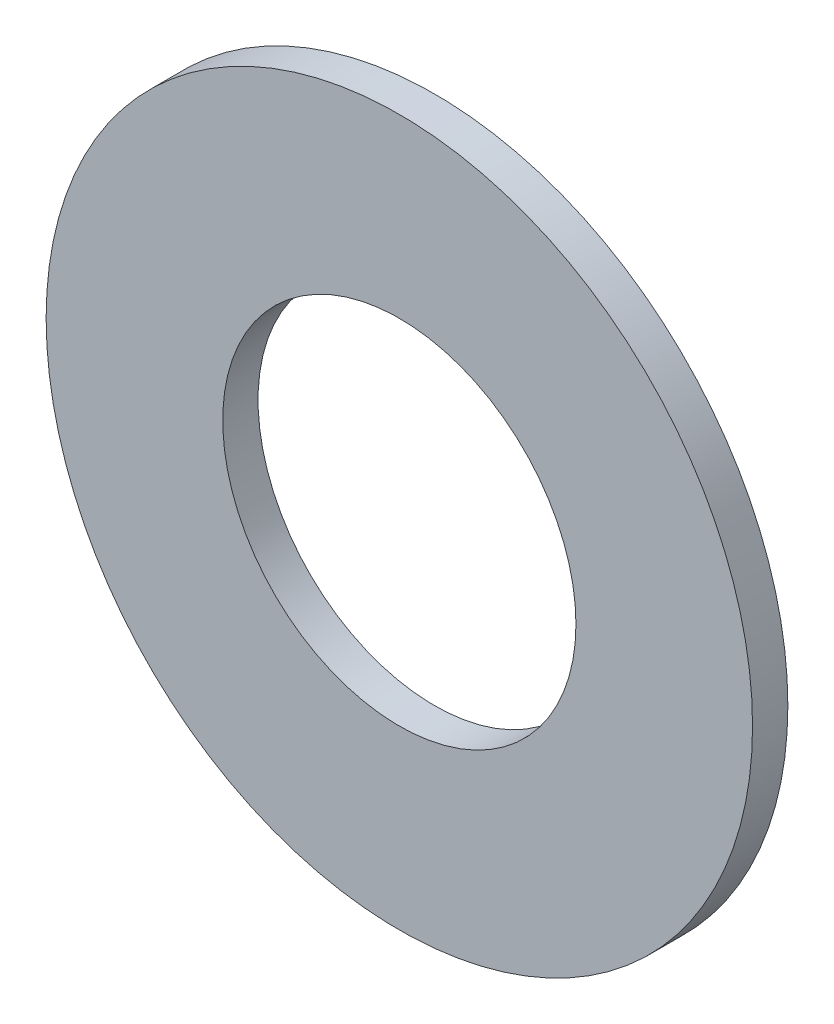
SolidWorks part; units mm, degrees
material "Литая нержавеющая сталь"
ref_plane "Спереди" through (0, 0, 0) normal (0, 0, 1) x (1, 0, 0)
ref_plane "Сверху" through (0, 0, 0) normal (0, 1, 0) x (1, 0, 0)
ref_plane "Справа" through (0, 0, 0) normal (1, 0, 0) x (0, 0, -1)
sketch "Эскиз1" plane through (0, 0, 0) normal (0, 0, 1) x (1, 0, 0)
  circle A0 centre (0, 0) radius 20
  circle A1 centre (0, 0) radius 10
  dimension "D1" = 20
  dimension "D2" = 40
extrude "Вытянуть1" add sketch "Эскиз1" along normal blind 2
